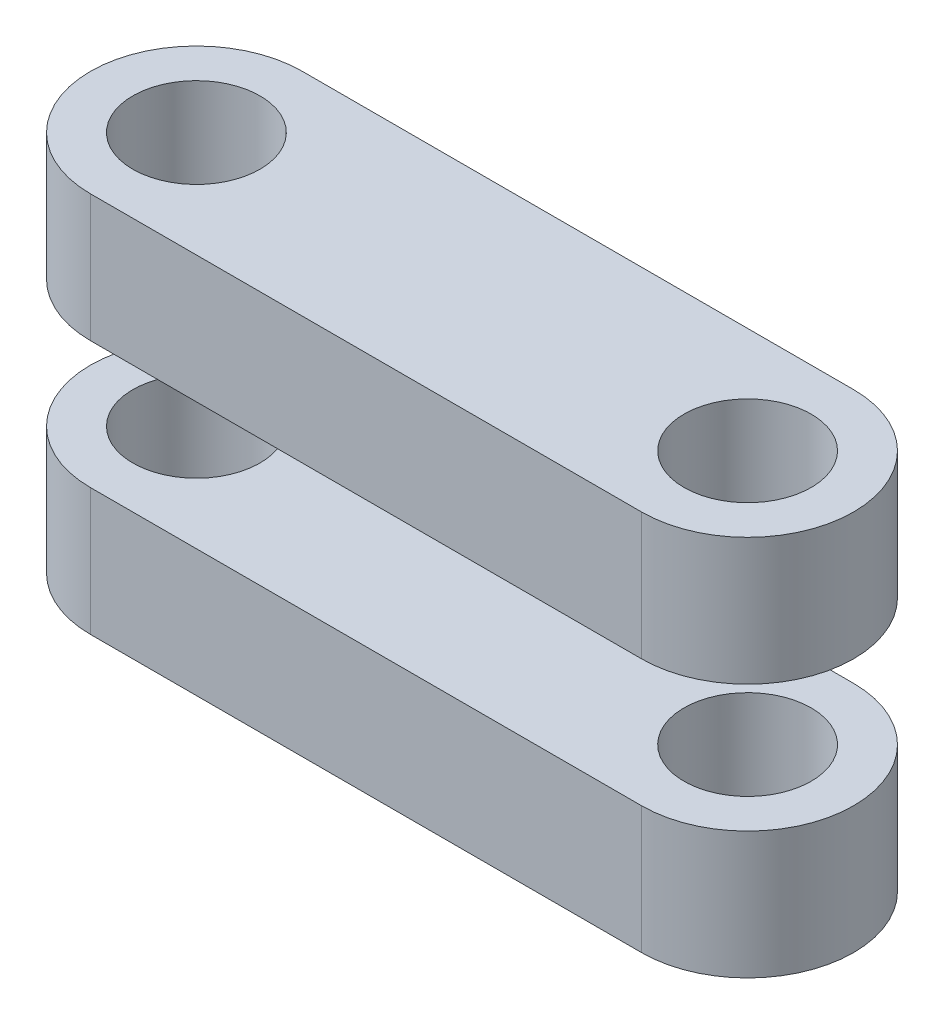
SolidWorks part; units mm, degrees
ref_plane "Front Plane" through (0, 0, 0) normal (0, 0, 1) x (1, 0, 0)
ref_plane "Top Plane" through (0, 0, 0) normal (0, 1, 0) x (1, 0, 0)
ref_plane "Right Plane" through (0, 0, 0) normal (1, 0, 0) x (0, 0, -1)
sketch "Sketch1" plane through (0, 0, 0) normal (0, 1, 0) x (1, 0, 0)
  line L0 (0, 2.5) -> (13, 2.5)
  line L1 (13, -2.5) -> (0, -2.5)
  circle A0 centre (0, 0) radius 1.5
  circle A1 centre (13, 0) radius 1.5
  arc A2 (0, 2.5) -> (0, -2.5) centre (0, 0) ccw
  arc A3 (13, -2.5) -> (13, 2.5) centre (13, 0) ccw
  dimension "D1" = 3
  dimension "D2" = 3
  dimension "D4" = 5
  dimension "D5" = 5
  dimension "D3" = 13
extrude "Boss-Extrude1" add sketch "Sketch1" along normal blind 9
sketch "Sketch2" plane through (0, 0, -2.5) normal (0, 0, -1) x (-1, 0, 0)
  line L0 (-6.5, 9) -> (-6.5, 0) construction
  line L1 (-13, 9) -> (0, 9) construction
  line L2 (-13, 0) -> (0, 0) construction
  line L3 (0, 4.5) -> (-13, 4.5) construction
  line L6 (0, 9) -> (0, 0) construction
  line L7 (-13, 9) -> (-13, 0) construction
  line L9 (-16, 3) -> (-10, 3)
  line L10 (-16, 3) -> (-16, 6)
  line L11 (-16, 6) -> (-10, 6)
  line L12 (-10, 3) -> (-10, 6)
  line L13 (-16, 3) -> (-10, 6) construction
  line L14 (-16, 6) -> (-10, 3) construction
  line L15 (-3, 3) -> (3, 3)
  line L16 (-3, 3) -> (-3, 6)
  line L17 (-3, 6) -> (3, 6)
  line L18 (3, 3) -> (3, 6)
  line L19 (-3, 3) -> (3, 6) construction
  line L20 (-3, 6) -> (3, 3) construction
  dimension "D1" = 3
  dimension "D2" = 3
  dimension "D3" = 6
  dimension "D4" = 6
extrude "Cut-Extrude1" cut sketch "Sketch2" against normal through all
chamfer "Chamfer1" distance 1 angle 45 4 edges at (10, 4.5, 2.5) (3, 4.5, 2.5) (10, 4.5, -2.5) (3, 4.5, -2.5)
sketch "Sketch3" plane through (3, 0, 0) normal (-1, 0, 0) x (0, 0, 1)
  line L1 (-2.5, 6) -> (2.5, 6)
  line L2 (-2.5, 6) -> (-2.5, 3)
  line L3 (-2.5, 3) -> (2.5, 3)
  line L4 (2.5, 6) -> (2.5, 3)
extrude "Cut-Extrude2" cut sketch "Sketch3" against normal blind 9
